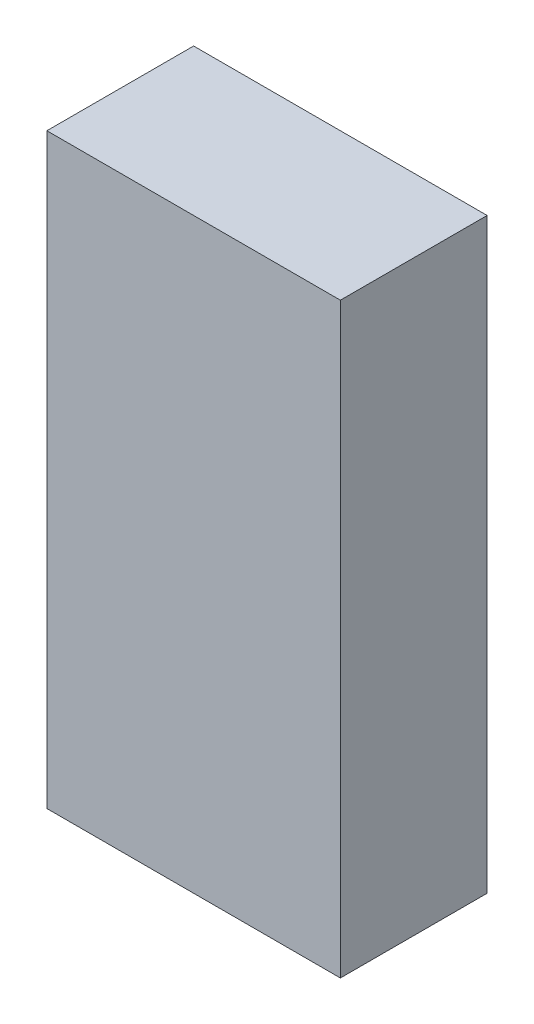
SolidWorks part; units mm, degrees
ref_plane "정면" through (0, 0, 0) normal (0, 0, 1) x (1, 0, 0)
ref_plane "윗면" through (0, 0, 0) normal (0, 1, 0) x (1, 0, 0)
ref_plane "우측면" through (0, 0, 0) normal (1, 0, 0) x (0, 0, -1)
sketch "스케치1" plane through (0, 0, 0) normal (0, 0, 1) x (1, 0, 0)
  line L0 (0, 0) -> (-11.3627, 0)
  line L1 (13.3705, -115) -> (13.3705, -20)
  line L2 (13.3705, -115) -> (13.3705, 20)
  line L3 (13.3705, 20) -> (33.3705, 20)
  line L4 (33.3705, -20) -> (33.3705, 20)
  line L6 (13.3705, 20) -> (13.3705, 115)
  line L14 (13.3705, -20) -> (33.3705, -20)
  point P7 (0, 0)
  dimension "D1" = 40
  dimension "D4" = 20
extrude "보스-돌출1" add sketch "스케치1" along normal blind 10
sketch "스케치2" plane through (0, 0, 10) normal (0, 0, 1) x (1, 0, 0)
  line L0 (33.3705, -20) -> (33.3705, 20) construction
  circle A0 centre (23.3705, 0) radius 3.8343
  dimension "D1" = 10
